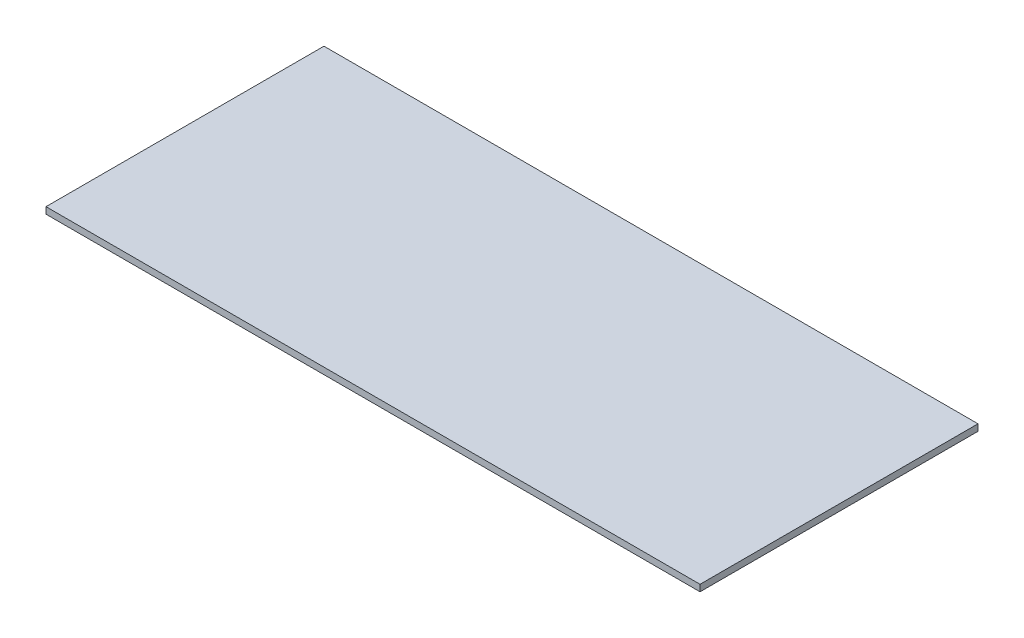
SolidWorks part; units mm, degrees
ref_plane "Front Plane" through (0, 0, 0) normal (0, 0, 1) x (1, 0, 0)
ref_plane "Top Plane" through (0, 0, 0) normal (0, 1, 0) x (1, 0, 0)
ref_plane "Right Plane" through (0, 0, 0) normal (1, 0, 0) x (0, 0, -1)
ref_plane "Plane1" through (0, 19, 0) normal (0, 1, 0) x (1, 0, 0)
sketch "Sketch1" plane through (0, 19, 0) normal (0, 1, 0) x (1, 0, 0)
  line L0 (100, -260) -> (500, -260)
  line L1 (500, -260) -> (500, -430)
  line L2 (500, -430) -> (100, -430)
  line L3 (100, -430) -> (100, -260)
extrude "Boss-Extrude1" add sketch "Sketch1" along normal blind 4
